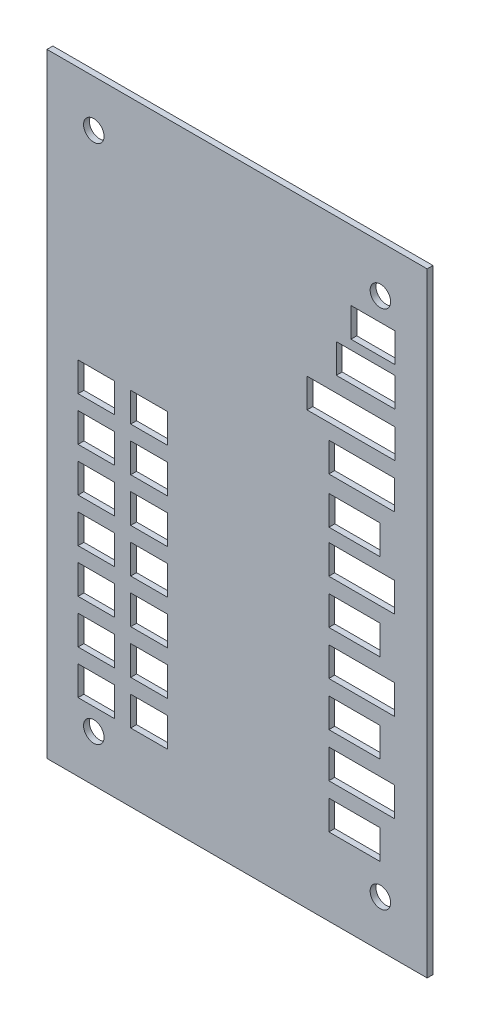
SolidWorks part; units mm, degrees
ref_plane "前视基准面" through (0, 0, 0) normal (0, 0, 1) x (1, 0, 0)
ref_plane "上视基准面" through (0, 0, 0) normal (0, 1, 0) x (1, 0, 0)
ref_plane "右视基准面" through (0, 0, 0) normal (1, 0, 0) x (0, 0, -1)
sketch "草图1" plane through (0, 0, 0) normal (0, 0, 1) x (1, 0, 0)
  line L1 (25, 125) -> (80, 125)
  line L2 (25, 125) -> (25, 30)
  line L3 (25, 30) -> (80, 30)
  line L4 (80, 125) -> (80, 30)
extrude "凸台-拉伸1" add sketch "草图1" along normal blind 1 contours L2 L3 L4 L1
sketch "草图3" plane through (0, 0, 1) normal (0, 0, 1) x (1, 0, 0)
  line L1 (79.462, 118.07) -> (71.962, 118.07)
  line L2 (79.462, 118.07) -> (79.462, 113.07)
  line L3 (79.462, 113.07) -> (71.962, 113.07)
  line L4 (71.962, 118.07) -> (71.962, 113.07)
  line L5 (79.462, 111.466) -> (69.462, 111.466)
  line L6 (79.462, 111.466) -> (79.462, 106.466)
  line L7 (79.462, 106.466) -> (69.462, 106.466)
  line L8 (69.462, 111.466) -> (69.462, 106.466)
  line L9 (79.462, 103.846) -> (64.462, 103.846)
  line L10 (79.462, 103.846) -> (79.462, 98.846)
  line L11 (79.462, 98.846) -> (64.462, 98.846)
  line L12 (64.462, 103.846) -> (64.462, 98.846)
  line L13 (79.434, 96.226) -> (68.184, 96.226)
  line L14 (79.434, 96.226) -> (79.434, 91.226)
  line L15 (79.434, 91.226) -> (68.184, 91.226)
  line L16 (68.184, 96.226) -> (68.184, 91.226)
  line L17 (76.954, 88.352) -> (68.204, 88.352)
  line L18 (76.954, 88.352) -> (76.954, 83.352)
  line L19 (76.954, 83.352) -> (68.204, 83.352)
  line L20 (68.204, 88.352) -> (68.204, 83.352)
  line L21 (79.434, 81.0831) -> (68.184, 81.0831)
  line L22 (79.434, 81.0831) -> (79.434, 76.0831)
  line L23 (79.434, 76.0831) -> (68.184, 76.0831)
  line L24 (68.184, 81.0831) -> (68.184, 76.0831)
  line L25 (76.943, 73.5117) -> (68.193, 73.5117)
  line L26 (76.943, 73.5117) -> (76.943, 68.5117)
  line L27 (76.943, 68.5117) -> (68.193, 68.5117)
  line L28 (68.193, 73.5117) -> (68.193, 68.5117)
  line L29 (79.434, 65.9403) -> (68.184, 65.9403)
  line L30 (79.434, 65.9403) -> (79.434, 60.9403)
  line L31 (79.434, 60.9403) -> (68.184, 60.9403)
  line L32 (68.184, 65.9403) -> (68.184, 60.9403)
  line L33 (76.943, 58.3689) -> (68.193, 58.3689)
  line L34 (76.943, 58.3689) -> (76.943, 53.3689)
  line L35 (76.943, 53.3689) -> (68.193, 53.3689)
  line L36 (68.193, 58.3689) -> (68.193, 53.3689)
  line L37 (79.434, 50.7974) -> (68.184, 50.7974)
  line L38 (79.434, 50.7974) -> (79.434, 45.7974)
  line L39 (79.434, 45.7974) -> (68.184, 45.7974)
  line L40 (68.184, 50.7974) -> (68.184, 45.7974)
  line L41 (76.943, 43.226) -> (68.193, 43.226)
  line L42 (76.943, 43.226) -> (76.943, 38.226)
  line L43 (76.943, 38.226) -> (68.193, 38.226)
  line L44 (68.193, 43.226) -> (68.193, 38.226)
  line L45 (40.566, 86.674) -> (34.316, 86.674)
  line L46 (40.566, 86.674) -> (40.566, 81.674)
  line L47 (40.566, 81.674) -> (34.316, 81.674)
  line L48 (34.316, 86.674) -> (34.316, 81.674)
  line L49 (31.566, 86.674) -> (25.316, 86.674)
  line L50 (31.566, 86.674) -> (31.566, 81.674)
  line L51 (31.566, 81.674) -> (25.316, 81.674)
  line L52 (25.316, 86.674) -> (25.316, 81.674)
  line L53 (40.566, 79.174) -> (34.316, 79.174)
  line L54 (40.566, 79.174) -> (40.566, 74.174)
  line L55 (40.566, 74.174) -> (34.316, 74.174)
  line L56 (34.316, 79.174) -> (34.316, 74.174)
  line L57 (31.566, 79.174) -> (25.316, 79.174)
  line L58 (31.566, 79.174) -> (31.566, 74.174)
  line L59 (31.566, 74.174) -> (25.316, 74.174)
  line L60 (25.316, 79.174) -> (25.316, 74.174)
  line L61 (40.566, 71.674) -> (34.316, 71.674)
  line L62 (40.566, 71.674) -> (40.566, 66.674)
  line L63 (40.566, 66.674) -> (34.316, 66.674)
  line L64 (34.316, 71.674) -> (34.316, 66.674)
  line L65 (31.566, 71.674) -> (25.316, 71.674)
  line L66 (31.566, 71.674) -> (31.566, 66.674)
  line L67 (31.566, 66.674) -> (25.316, 66.674)
  line L68 (25.316, 71.674) -> (25.316, 66.674)
  line L69 (40.566, 64.174) -> (34.316, 64.174)
  line L70 (40.566, 64.174) -> (40.566, 59.174)
  line L71 (40.566, 59.174) -> (34.316, 59.174)
  line L72 (34.316, 64.174) -> (34.316, 59.174)
  line L73 (31.566, 64.174) -> (25.316, 64.174)
  line L74 (31.566, 64.174) -> (31.566, 59.174)
  line L75 (31.566, 59.174) -> (25.316, 59.174)
  line L76 (25.316, 64.174) -> (25.316, 59.174)
  line L77 (40.566, 56.674) -> (34.316, 56.674)
  line L78 (40.566, 56.674) -> (40.566, 51.674)
  line L79 (40.566, 51.674) -> (34.316, 51.674)
  line L80 (34.316, 56.674) -> (34.316, 51.674)
  line L81 (31.566, 56.674) -> (25.316, 56.674)
  line L82 (31.566, 56.674) -> (31.566, 51.674)
  line L83 (31.566, 51.674) -> (25.316, 51.674)
  line L84 (25.316, 56.674) -> (25.316, 51.674)
  line L85 (40.566, 49.174) -> (34.316, 49.174)
  line L86 (40.566, 49.174) -> (40.566, 44.174)
  line L87 (40.566, 44.174) -> (34.316, 44.174)
  line L88 (34.316, 49.174) -> (34.316, 44.174)
  line L89 (31.566, 49.174) -> (25.316, 49.174)
  line L90 (31.566, 49.174) -> (31.566, 44.174)
  line L91 (31.566, 44.174) -> (25.316, 44.174)
  line L92 (25.316, 49.174) -> (25.316, 44.174)
  line L93 (40.566, 41.674) -> (34.316, 41.674)
  line L94 (40.566, 41.674) -> (40.566, 36.674)
  line L95 (40.566, 36.674) -> (34.316, 36.674)
  line L96 (34.316, 41.674) -> (34.316, 36.674)
  line L97 (31.566, 41.674) -> (25.316, 41.674)
  line L98 (31.566, 41.674) -> (31.566, 36.674)
  line L99 (31.566, 36.674) -> (25.316, 36.674)
  line L100 (25.316, 41.674) -> (25.316, 36.674)
  circle A0 centre (76.962, 115.57) radius 0.25 construction
  circle A1 centre (74.462, 115.57) radius 0.25 construction
  circle A2 centre (75.712, 115.57) radius 0.25 construction
  circle A3 centre (38.066, 46.674) radius 0.25 construction
  circle A4 centre (36.816, 46.674) radius 0.25 construction
  circle A5 centre (29.066, 46.674) radius 0.25 construction
  circle A6 centre (27.816, 46.674) radius 0.25 construction
  circle A7 centre (38.066, 39.174) radius 0.25 construction
  circle A8 centre (36.816, 39.174) radius 0.25 construction
  circle A9 centre (29.066, 39.174) radius 0.25 construction
  circle A10 centre (76.962, 108.966) radius 0.25 construction
  circle A11 centre (71.962, 108.966) radius 0.25 construction
  circle A12 centre (76.962, 101.346) radius 0.25 construction
  circle A13 centre (66.962, 101.346) radius 0.25 construction
  circle A14 centre (76.934, 93.726) radius 0.25 construction
  circle A15 centre (70.684, 93.726) radius 0.25 construction
  circle A16 centre (73.184, 93.726) radius 0.25 construction
  circle A17 centre (71.934, 93.726) radius 0.25 construction
  circle A18 centre (74.454, 85.852) radius 0.25 construction
  circle A19 centre (70.704, 85.852) radius 0.25 construction
  circle A20 centre (73.204, 85.852) radius 0.25 construction
  circle A21 centre (76.934, 78.5831) radius 0.25 construction
  circle A22 centre (70.684, 78.5831) radius 0.25 construction
  circle A23 centre (74.443, 71.0117) radius 0.25 construction
  circle A24 centre (70.693, 71.0117) radius 0.25 construction
  circle A25 centre (73.193, 71.0117) radius 0.25 construction
  circle A26 centre (76.934, 63.4403) radius 0.25 construction
  circle A27 centre (70.684, 63.4403) radius 0.25 construction
  circle A28 centre (74.434, 63.4403) radius 0.25 construction
  circle A29 centre (75.684, 63.4403) radius 0.25 construction
  circle A30 centre (74.443, 55.8689) radius 0.25 construction
  circle A31 centre (70.693, 55.8689) radius 0.25 construction
  circle A32 centre (73.193, 55.8689) radius 0.25 construction
  circle A33 centre (76.934, 48.2974) radius 0.25 construction
  circle A34 centre (70.684, 48.2974) radius 0.25 construction
  circle A35 centre (73.184, 48.2974) radius 0.25 construction
  circle A36 centre (74.434, 48.2974) radius 0.25 construction
  circle A37 centre (74.443, 40.726) radius 0.25 construction
  circle A38 centre (70.693, 40.726) radius 0.25 construction
  circle A39 centre (73.193, 40.726) radius 0.25 construction
  circle A40 centre (38.066, 84.174) radius 0.25 construction
  circle A41 centre (36.816, 84.174) radius 0.25 construction
  circle A42 centre (29.066, 84.174) radius 0.25 construction
  circle A43 centre (27.816, 84.174) radius 0.25 construction
  circle A44 centre (29.066, 76.674) radius 0.25 construction
  circle A45 centre (27.816, 76.674) radius 0.25 construction
  circle A46 centre (38.066, 76.674) radius 0.25 construction
  circle A47 centre (36.816, 76.674) radius 0.25 construction
  circle A48 centre (38.066, 76.674) radius 0.25 construction
  circle A49 centre (38.066, 69.174) radius 0.25 construction
  circle A50 centre (36.816, 69.174) radius 0.25 construction
  circle A51 centre (29.066, 69.174) radius 0.25 construction
  circle A52 centre (27.816, 69.174) radius 0.25 construction
  circle A53 centre (38.066, 61.674) radius 0.25 construction
  circle A54 centre (36.816, 61.674) radius 0.25 construction
  circle A55 centre (29.066, 61.674) radius 0.25 construction
  circle A56 centre (27.816, 61.674) radius 0.25 construction
  circle A57 centre (38.066, 54.174) radius 0.25 construction
  circle A58 centre (36.816, 54.174) radius 0.25 construction
  circle A59 centre (29.066, 54.174) radius 0.25 construction
  circle A60 centre (27.816, 54.174) radius 0.25 construction
  circle A61 centre (29.066, 54.174) radius 0.25 construction
  circle A62 centre (27.816, 39.174) radius 0.25 construction
  dimension "D1" = 2.5
  dimension "D4" = 2.5
  dimension "D5" = 2.5
  dimension "D8" = 2.5
  dimension "D9" = 2.5
  dimension "D11" = 2.5
  dimension "D12" = 2.5
  dimension "D13" = 2.5
  dimension "D7" = 2.5
  dimension "D10" = 2.5
  dimension "D16" = 2.5
  dimension "D17" = 2.5
  dimension "D18" = 2.5
  dimension "D19" = 2.5
  dimension "D20" = 2.5
  dimension "D21" = 2.5
  dimension "D22" = 2.5
  dimension "D23" = 2.5
  dimension "D24" = 2.5
  dimension "D25" = 2.5
  dimension "D26" = 2.5
  dimension "D28" = 2.5
  dimension "D29" = 2.5
  dimension "D30" = 2.5
  dimension "D31" = 2.5
  dimension "D32" = 2.5
  dimension "D33" = 2.5
  dimension "D34" = 2.5
  dimension "D35" = 2.5
  dimension "D36" = 2.5
  dimension "D37" = 2.5
  dimension "D38" = 2.5
  dimension "D39" = 2.5
  dimension "D40" = 2.5
  dimension "D41" = 2.5
  dimension "D42" = 2.5
  dimension "D44" = 2.5
  dimension "D45" = 2.5
  dimension "D46" = 2.5
  dimension "D47" = 2.5
  dimension "D48" = 2.5
  dimension "D49" = 2.5
  dimension "D51" = 2.5
  dimension "D52" = 2.5
  dimension "D53" = 2.5
  dimension "D54" = 2.5
  dimension "D55" = 2.5
  dimension "D56" = 2.5
  dimension "D57" = 2.5
  dimension "D58" = 2.5
  dimension "D59" = 2.5
  dimension "D60" = 2.5
  dimension "D61" = 2.5
  dimension "D62" = 2.5
  dimension "D63" = 2.5
  dimension "D64" = 2.5
  dimension "D65" = 2.5
  dimension "D66" = 2.5
  dimension "D67" = 2.5
  dimension "D68" = 2.5
  dimension "D69" = 2.5
  dimension "D70" = 2.5
  dimension "D71" = 2.5
  dimension "D72" = 2.5
  dimension "D74" = 2.5
  dimension "D75" = 2.5
  dimension "D76" = 2.5
  dimension "D77" = 2.5
  dimension "D78" = 2.5
  dimension "D79" = 2.5
  dimension "D80" = 2.5
  dimension "D82" = 2.5
  dimension "D83" = 2.5
  dimension "D84" = 2.5
  dimension "D85" = 2.5
  dimension "D86" = 2.5
  dimension "D87" = 2.5
  dimension "D88" = 2.5
  dimension "D89" = 2.5
  dimension "D91" = 2.5
  dimension "D92" = 2.5
  dimension "D93" = 2.5
  dimension "D94" = 2.5
  dimension "D95" = 2.5
  dimension "D96" = 2.5
  dimension "D97" = 2.5
  dimension "D98" = 2.5
  dimension "D99" = 2.5
  dimension "D100" = 2.5
  dimension "D2" = 2.5
  dimension "D3" = 2.5
  dimension "D6" = 2.5
  dimension "D14" = 2.5
  dimension "D15" = 2.5
  dimension "D27" = 2.5
  dimension "D43" = 2.5
  dimension "D50" = 2.5
  dimension "D73" = 2.5
  dimension "D81" = 2.5
  dimension "D90" = 2.5
extrude "切除-拉伸1" cut sketch "草图3" against normal blind 1
sketch "草图7" plane through (0, 0, 1) normal (0, 0, 1) x (1, 0, 0)
  circle A0 centre (77, 122) radius 1.75
  circle A1 centre (28, 122) radius 1.75
  circle A2 centre (77, 33) radius 1.75
  circle A3 centre (28, 33) radius 1.75
  dimension "D1" = 3.5
  dimension "D2" = 3.5
  dimension "D3" = 3.5
  dimension "D4" = 3.5
extrude "切除-拉伸4" cut sketch "草图7" against normal blind 1
sketch "草图8" plane through (0, 125, 0) normal (0, 1, 0) x (1, 0, 0)
  line L1 (25, 0) -> (80, 0)
  line L2 (25, 0) -> (25, -1)
  line L3 (25, -1) -> (80, -1)
  line L4 (80, 0) -> (80, -1)
extrude "凸台-拉伸2" add sketch "草图8" along normal blind 5
sketch "草图9" plane through (0, 30, 0) normal (0, -1, 0) x (1, 0, 0)
  line L1 (25, 0) -> (80, 0)
  line L2 (25, 0) -> (25, 1)
  line L3 (25, 1) -> (80, 1)
  line L4 (80, 0) -> (80, 1)
extrude "凸台-拉伸3" add sketch "草图9" along normal blind 5
sketch "草图10" plane through (25, 0, 0) normal (-1, 0, 0) x (0, 0, 1)
  line L1 (1, 130) -> (0, 130)
  line L2 (1, 130) -> (1, 25)
  line L3 (1, 25) -> (0, 25)
  line L4 (0, 130) -> (0, 25)
extrude "凸台-拉伸4" add sketch "草图10" along normal blind 5
sketch "草图11" plane through (80, 0, 0) normal (1, 0, 0) x (0, 0, -1)
  line L1 (0, 25) -> (-1, 25)
  line L2 (0, 25) -> (0, 130)
  line L3 (0, 130) -> (-1, 130)
  line L4 (-1, 25) -> (-1, 130)
extrude "凸台-拉伸5" add sketch "草图11" along normal blind 5
